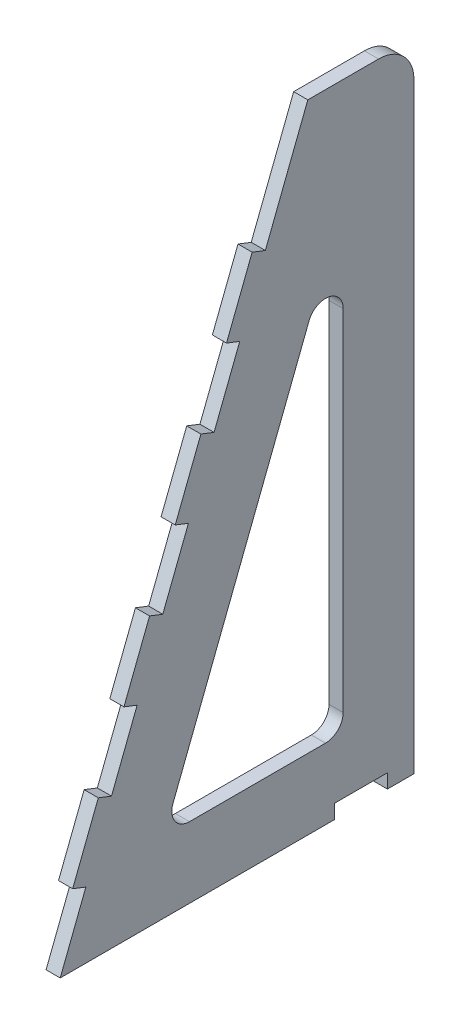
SolidWorks part; units mm, degrees
ref_plane "Piano frontale" through (0, 0, 0) normal (0, 0, 1) x (1, 0, 0)
ref_plane "Piano superiore" through (0, 0, 0) normal (0, 1, 0) x (1, 0, 0)
ref_plane "Piano destro" through (0, 0, 0) normal (1, 0, 0) x (0, 0, -1)
sketch "Schizzo1" plane through (0, 0, 0) normal (1, 0, 0) x (0, 0, -1)
  line L0 (0, 0) -> (100, 0)
  line L1 (100, 0) -> (100, 180)
  line L3 (0, 0) -> (70, 180)
  line L4 (70, 180) -> (100, 180)
  line L5 (80, 150.5337) -> (80, 150.5337)
  line L6 (77.5, 0) -> (92.5, 0)
  line L7 (77.5, 0) -> (77.5, 4)
  line L8 (77.5, 4) -> (92.5, 4)
  line L9 (92.5, 0) -> (92.5, 4)
  line L10 (80, 20) -> (80, 150.5337)
  line L11 (29.2369, 20) -> (80, 20)
  line L12 (29.2369, 20) -> (80, 150.5337)
  dimension "D1" = 100
  dimension "D2" = 180
  dimension "D3" = 30
  dimension "D4" = 4
  dimension "D5" = 15
  dimension "D6" = 7.5
  dimension "D7" = 20
extrude "Estrusione-Estrusione1" add sketch "Schizzo1" along normal blind 4 contours L9 L0 L1 L4 L3 L7 L8
sketch "Schizzo2" plane through (4, 0, 0) normal (1, 0, 0) x (0, 0, -1)
  line L0 (7.2489, 18.6401) -> (3.5209, 20.0899)
  line L2 (3.5209, 20.0899) -> (10.7698, 38.73)
  line L3 (10.7698, 38.73) -> (14.4979, 37.2802)
  line L4 (14.4979, 37.2802) -> (7.2489, 18.6401)
  line L5 (28.9957, 74.5604) -> (21.7468, 55.9203)
  line L6 (21.7468, 55.9203) -> (18.0188, 57.3701)
  line L7 (18.0188, 57.3701) -> (25.2677, 76.0102)
  line L8 (25.2677, 76.0102) -> (28.9957, 74.5604)
  line L9 (43.4936, 111.8406) -> (36.2446, 93.2005)
  line L10 (36.2446, 93.2005) -> (32.5166, 94.6503)
  line L11 (32.5166, 94.6503) -> (39.7655, 113.2903)
  line L12 (39.7655, 113.2903) -> (43.4936, 111.8406)
  line L13 (57.9914, 149.1207) -> (50.7425, 130.4807)
  line L14 (50.7425, 130.4807) -> (47.0145, 131.9304)
  line L15 (47.0145, 131.9304) -> (54.2634, 150.5705)
  line L16 (54.2634, 150.5705) -> (57.9914, 149.1207)
  line L18 (0, 0) -> (70, 180) construction
  dimension "D1" = 20
  dimension "D2" = 4
  dimension "D3" = 20
  dimension "D4" = 4
extrude "Estrusione-Estrusione2" add sketch "Schizzo2" against normal blind 4
fillet "Raccordo2" radius 10 1 edges at (2, 180, -100)
fillet "Raccordo3" radius 5 3 edges at (2, 20, -29.2369) (2, 20, -80) (2, 150.5337, -80)
